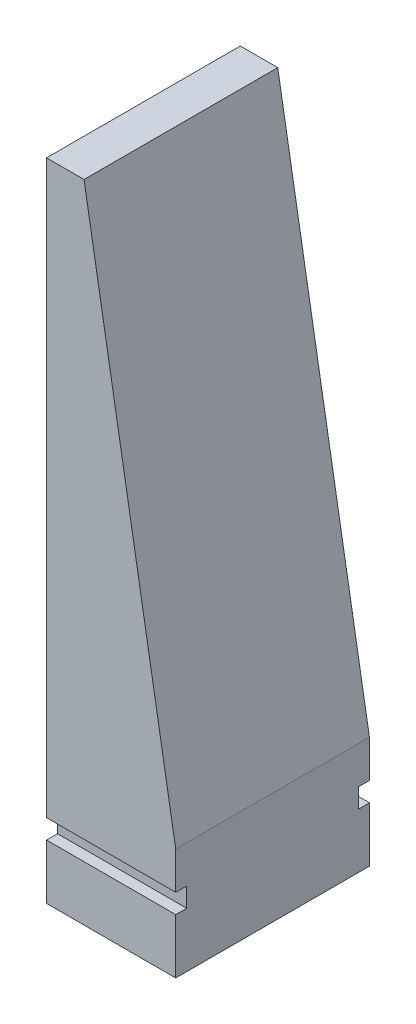
SolidWorks part; units mm, degrees
material "201 Annealed Stainless Steel (SS)"
ref_plane "Front Plane" through (0, 0, 0) normal (0, 0, 1) x (1, 0, 0)
ref_plane "Top Plane" through (0, 0, 0) normal (0, 1, 0) x (1, 0, 0)
ref_plane "Right Plane" through (0, 0, 0) normal (1, 0, 0) x (0, 0, -1)
sketch "Sketch1" plane through (0, 0, 0) normal (1, 0, 0) x (0, 0, -1)
  line L1 (7.5, 0) -> (-7.5, 0)
  line L2 (7.5, 0) -> (7.5, 50)
  line L3 (7.5, 50) -> (-7.5, 50)
  line L4 (-7.5, 0) -> (-7.5, 50)
  point P4 (0, 0)
  dimension "D1" = 50
  dimension "D2" = 15
extrude "Boss-Extrude1" add sketch "Sketch1" along normal blind 10
sketch "Sketch2" plane through (10, 0, 0) normal (1, 0, 0) x (0, 0, -1)
  line L0 (-7.5, 10) -> (7.5, 10) construction
  line L1 (-7.5, 50) -> (-7.5, 0) construction
  line L2 (7.5, 0) -> (7.5, 50) construction
  line L3 (-7.5, 0) -> (7.5, 0) construction
  line L4 (0, 10) -> (0, 0) construction
  line L5 (-7.5, 5.75) -> (-6.65, 5.75)
  line L6 (-6.65, 5.75) -> (-6.65, 4.25)
  line L7 (-6.65, 4.25) -> (-7.5, 4.25)
  line L8 (-6.65, 5) -> (0, 5) construction
  line L9 (-7.5, 5.75) -> (-7.5, 4.25)
  line L10 (7.5, 5.75) -> (6.65, 5.75)
  line L11 (6.65, 5.75) -> (6.65, 4.25)
  line L12 (6.65, 4.25) -> (7.5, 4.25)
  line L13 (7.5, 5.75) -> (7.5, 4.25)
  dimension "D1" = 10
  dimension "D2" = 0.85
  dimension "D3" = 1.5
extrude "Cut-Extrude1" cut sketch "Sketch2" against normal through all
sketch "Sketch3" plane through (0, 0, 7.5) normal (0, 0, 1) x (1, 0, 0)
  line L0 (2.9012, 50) -> (10, 8.6489)
  line L1 (10, 50) -> (0, 50) construction
  line L2 (10, 50) -> (10, 5.75) construction
  line L3 (10, 8.6489) -> (10, 50)
  line L4 (2.9012, 50) -> (10, 50)
  dimension "D1" = 2.9012
  dimension "D2" = 2.8989
extrude "Cut-Extrude3" cut sketch "Sketch3" against normal through all
